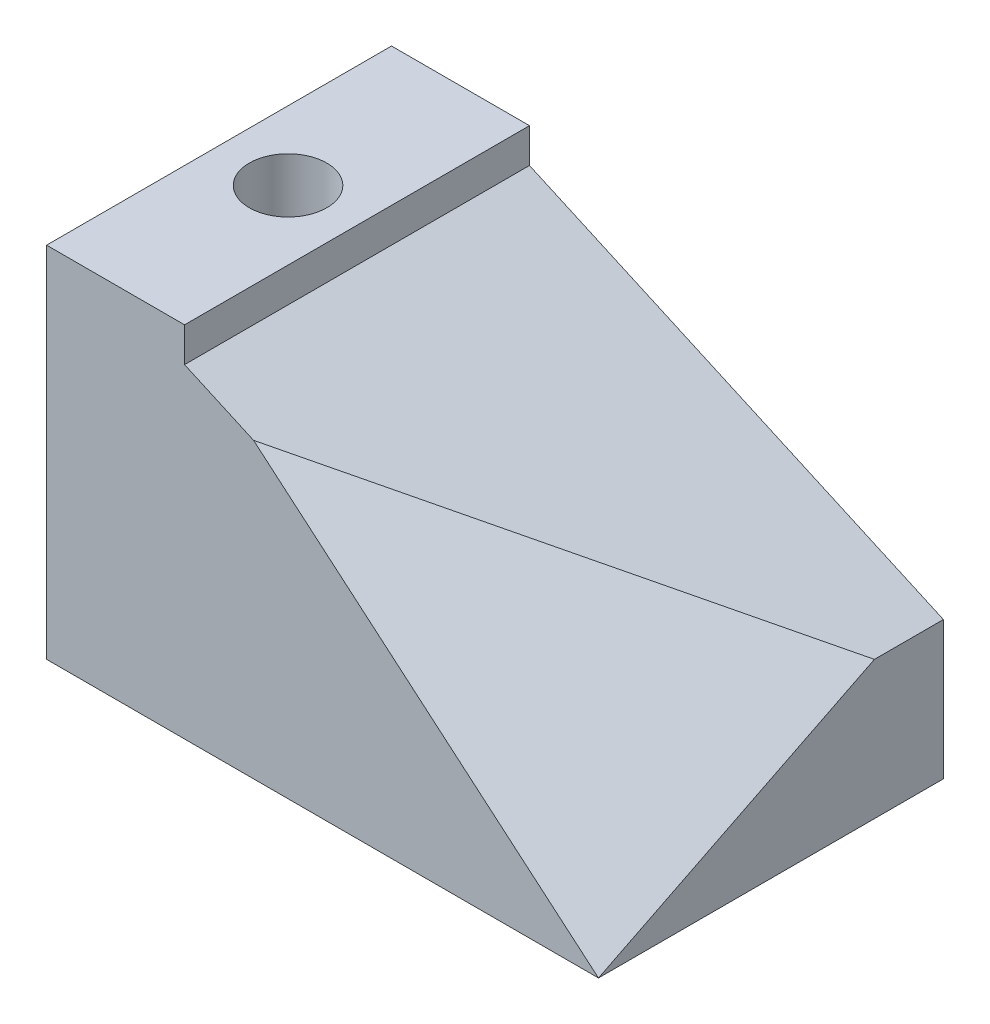
SolidWorks part; units mm, degrees
material "___"
ref_plane "Front Plane" through (0, 0, 0) normal (0, 0, 1) x (1, 0, 0)
ref_plane "Top Plane" through (0, 0, 0) normal (0, 1, 0) x (1, 0, 0)
ref_plane "Right Plane" through (0, 0, 0) normal (1, 0, 0) x (0, 0, -1)
sketch "Sketch1" plane through (0, 0, 0) normal (0, 0, 1) x (1, 0, 0)
  line L0 (0, 0) -> (0, -260)
  line L1 (0, -260) -> (400, -260)
  line L2 (400, -260) -> (400, -160)
  line L3 (400, -160) -> (100, -25)
  line L4 (100, -25) -> (100, 0)
  line L5 (100, 0) -> (0, 0)
  point P4 (138.408, 0)
  dimension "D1" = 260
  dimension "D2" = 400
  dimension "D3" = 25
  dimension "D4" = 100
  dimension "D5" = 100
extrude "Boss-Extrude1" add sketch "Sketch1" along normal mid plane 250
sketch3d "3DSketch1"
  line L0 (150, -47.5, 125) -> (400, -160, -75)
  line L1 (400, -160, 125) -> (100, -25, 125) construction
  line L2 (400, -160, 125) -> (400, -160, -125) construction
  line L3 (400, -160, -75) -> (400, -260, 125)
  line L4 (400, -260, 125) -> (150, -47.5, 125)
  line L5 (0, 0, 125) -> (0, -260, 125) construction
  line L7 (400, -260, -125) -> (400, -160, -125) construction
  point P7 (0, 0, 0)
  point P8 (297.1417, -386.5147, -80.1421)
  point P9 (400, -260, 125)
  point P10 (207.2106, -73.2448, 125)
  dimension "D1" = 150
  dimension "D2" = 50
extrude "Cut-Extrude1" cut sketch "3DSketch1" along direction (0, 1, 0) on the side against the normal blind 250
sketch "Sketch2" plane through (0, 0, 0) normal (0, 1, 0) x (1, 0, 0)
  line L0 (100, -125) -> (0, -125) construction
  line L1 (0, -125) -> (0, 125) construction
  circle A0 centre (50, 0) radius 28.1
  dimension "D3" = 56.2
  dimension "D1" = 125
  dimension "D2" = 50
extrude "Cut-Extrude2" cut sketch "Sketch2" against normal blind 150
